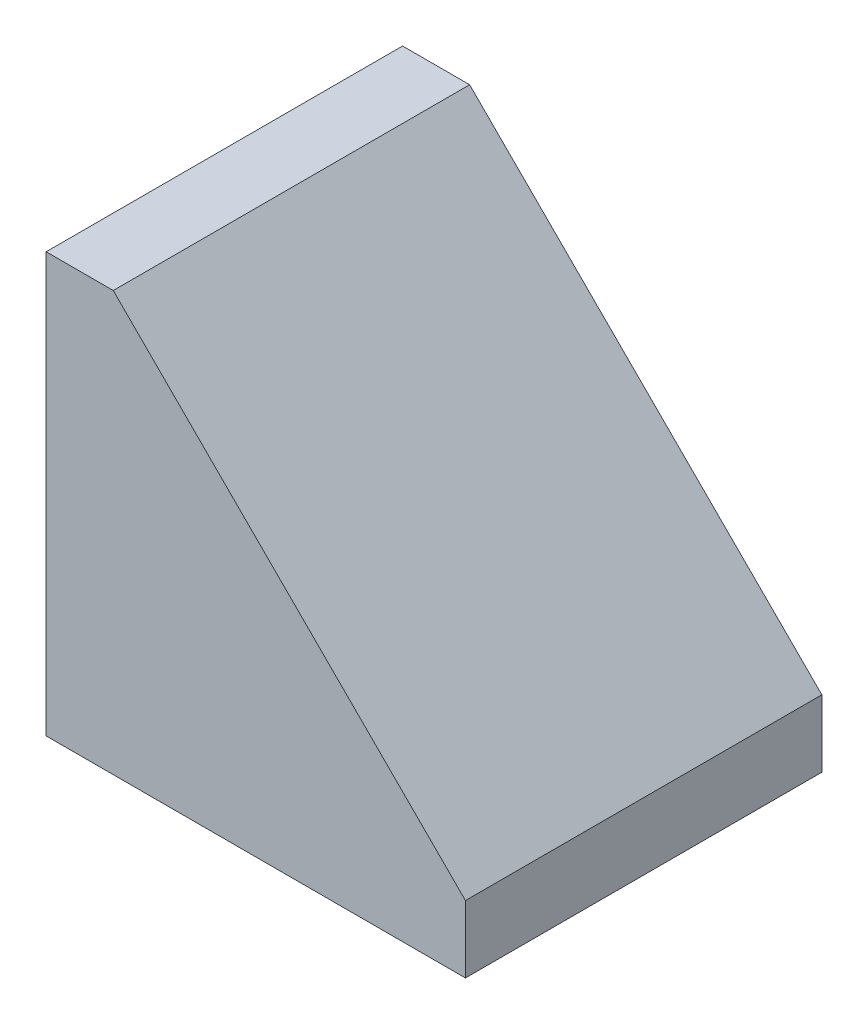
SolidWorks part; units mm, degrees
ref_plane "前基準面" through (0, 0, 0) normal (0, 0, 1) x (1, 0, 0)
ref_plane "上基準面" through (0, 0, 0) normal (0, 1, 0) x (1, 0, 0)
ref_plane "右基準面" through (0, 0, 0) normal (1, 0, 0) x (0, 0, -1)
sketch "草圖1" plane through (0, 0, 0) normal (0, 0, 1) x (1, 0, 0)
  line L0 (0, 20) -> (0, 0)
  line L1 (0, -55) -> (0, 55) construction
  line L2 (0, 0) -> (20, 0)
  line L3 (55, 0) -> (-55, 0) construction
  line L4 (20, 0) -> (20, 3.2)
  line L5 (20, 3.2) -> (3.2, 20)
  line L6 (3.2, 20) -> (0, 20)
  dimension "D1" = 20
  dimension "D2" = 20
  dimension "D3" = 3.2
  dimension "D4" = 3.2
extrude "填料-伸長1" add sketch "草圖1" along normal blind 17
